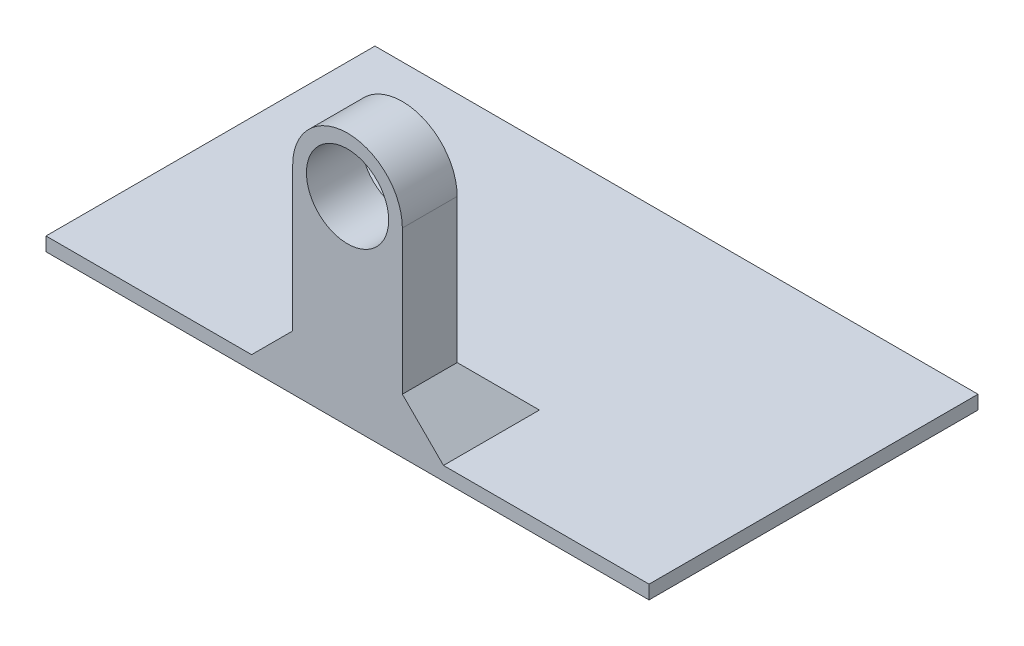
SolidWorks part; units mm, degrees
ref_plane "Plano frontal" through (0, 0, 0) normal (0, 0, 1) x (1, 0, 0)
ref_plane "Plano superior" through (0, 0, 0) normal (0, 1, 0) x (1, 0, 0)
ref_plane "Plano direito" through (0, 0, 0) normal (1, 0, 0) x (0, 0, -1)
sketch "Esboço1" plane through (0, 0, 0) normal (0, 1, 0) x (1, 0, 0)
  line L1 (110, -60) -> (-110, -60)
  line L2 (110, -60) -> (110, 60)
  line L3 (110, 60) -> (-110, 60)
  line L4 (-110, -60) -> (-110, 60)
  line L5 (110, -60) -> (-110, 60) construction
  line L6 (110, 60) -> (-110, -60) construction
  point P0 (0, 0)
  dimension "D1" = 220
  dimension "D2" = 120
extrude "Ressalto-extrusão1" add sketch "Esboço1" along normal blind 5
sketch "Esboço2" plane through (0, 0, 60) normal (0, 0, 1) x (1, 0, 0)
  line L0 (0, 0) -> (0, 5) construction
  line L1 (-110, 0) -> (110, 0) construction
  line L2 (-110, 5) -> (110, 5) construction
  line L3 (20, 72.5) -> (20, 5)
  line L4 (-20, 72.5) -> (-20, 5)
  line L5 (-20, 5) -> (20, 5)
  circle A0 centre (0, 72.5) radius 15
  arc A1 (20, 72.5) -> (-20, 72.5) centre (0, 72.5) ccw
  dimension "D1" = 30
  dimension "D2" = 40
  dimension "D3" = 67.5
extrude "Ressalto-extrusão2" add sketch "Esboço2" against normal blind 20
chamfer "Chanfro1" distance 15 angle 45 3 edges at (-20, 5, 50) (0, 5, 40) (20, 5, 50)
